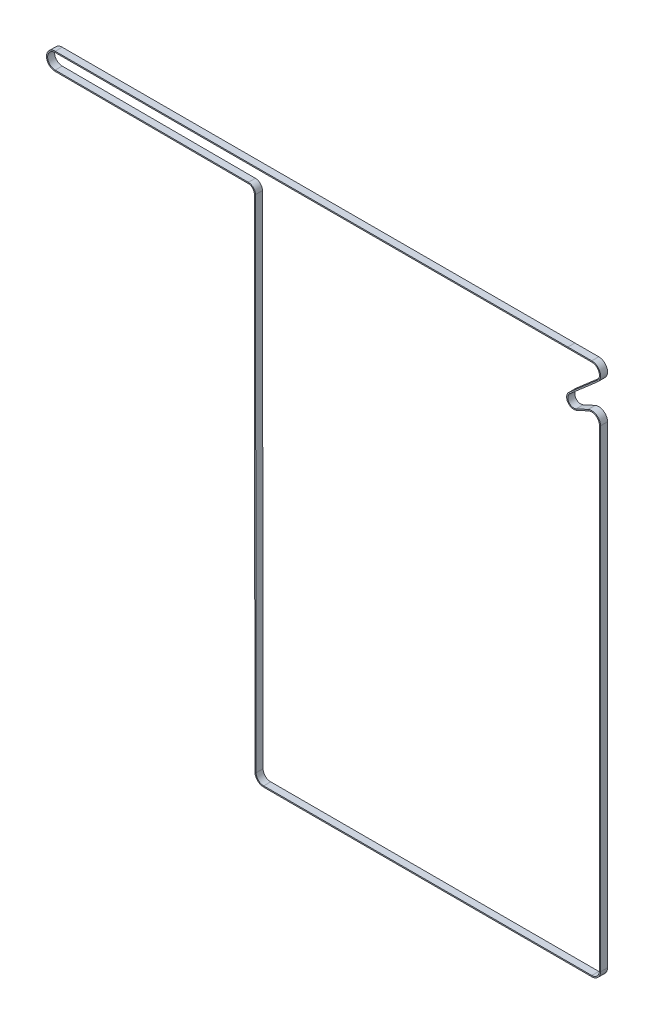
SolidWorks part; units mm, degrees
material "Rubber"
ref_plane "Front Plane" through (0, 0, 0) normal (0, 0, 1) x (1, 0, 0)
ref_plane "Top Plane" through (0, 0, 0) normal (0, 1, 0) x (1, 0, 0)
ref_plane "Right Plane" through (0, 0, 0) normal (1, 0, 0) x (0, 0, -1)
sketch "Sketch2" plane through (0, 0, 0) normal (0, 0, 1) x (1, 0, 0)
  line L0 (0, 0) -> (1, 0) construction
  line L1 (0, 0) -> (0, 1) construction
  line L2 (7.5339, -5.5598) -> (17.7813, -0.8894)
  line L3 (26.977, -6.8037) -> (27, -412.1503)
  line L4 (20.4972, -418.6507) -> (-260.7869, -418.5274)
  line L5 (-267.284, -412.0357) -> (-267.834, 16.9204)
  line L6 (-273.9256, 23.0226) -> (-439.5492, 23.5229)
  line L7 (-439.5321, 36.5229) -> (20.4976, 36.6959)
  line L8 (24.766, 25.2916) -> (0.99, 4.61)
  arc A0 (0.99, 4.61) -> (7.5339, -5.5598) centre (5, 0) ccw
  arc A1 (17.7813, -0.8894) -> (26.977, -6.8037) centre (20.477, -6.8041) cw
  arc A2 (27, -412.1503) -> (20.4972, -418.6507) centre (20.5, -412.1507) cw
  arc A3 (-260.7869, -418.5274) -> (-267.284, -412.0357) centre (-260.784, -412.0274) cw
  arc A4 (-267.834, 16.9204) -> (-273.9256, 23.0226) centre (-273.944, 16.9126) ccw
  arc A5 (-439.5492, 23.5229) -> (-439.5321, 36.5229) centre (-439.5296, 30.0229) cw
  arc A6 (20.4976, 36.6959) -> (24.766, 25.2916) centre (20.5, 30.1959) cw
sketch "Sketch3" plane through (0, 0, 0) normal (1, 0, 0) x (0, 0, -1)
  line L1 (-3, 37.6959) -> (3, 37.6959)
  line L2 (-3, 37.6959) -> (-3, 36.6959)
  line L3 (-3, 36.6959) -> (3, 36.6959)
  line L4 (3, 37.6959) -> (3, 36.6959)
  dimension "D1" = 6
  dimension "D2" = 1
sweep "Sweep1" add profiles "Sketch3" path "Sketch2"
